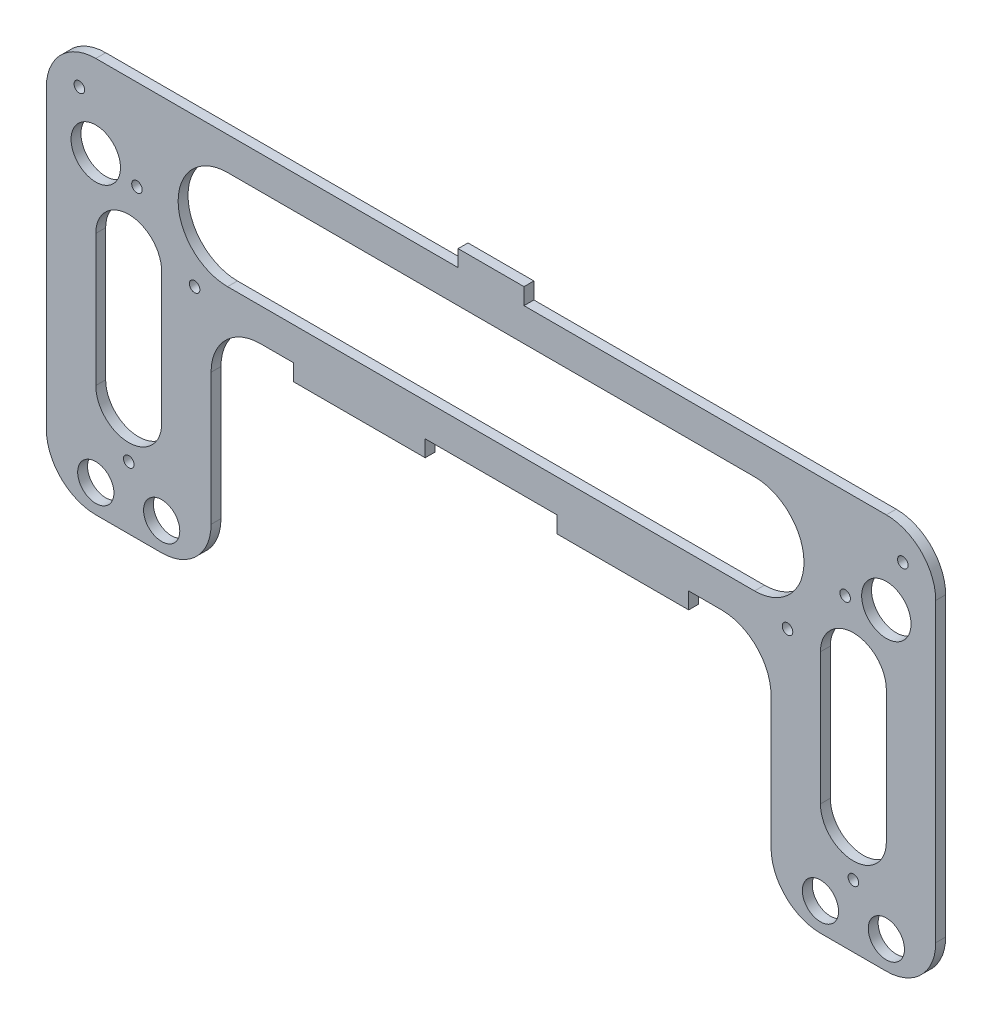
SolidWorks part; units mm, degrees
ref_plane "前视基准面" through (0, 0, 0) normal (0, 0, 1) x (1, 0, 0)
ref_plane "上视基准面" through (0, 0, 0) normal (0, 1, 0) x (1, 0, 0)
ref_plane "右视基准面" through (0, 0, 0) normal (1, 0, 0) x (0, 0, -1)
sketch "草图1" plane through (0, 0, 0) normal (0, 0, 1) x (1, 0, 0)
  line L0 (-120, 25) -> (-10, 25)
  line L4 (-125, 25) -> (0, 0) construction
  line L5 (125, 25) -> (0, 0) construction
  line L6 (0, 25) -> (0, 30) construction
  line L7 (-10, 25) -> (-10, 30)
  line L9 (-10, 30) -> (10, 30)
  line L10 (10, 25) -> (10, 30)
  line L11 (0, 25) -> (10, 30) construction
  line L12 (-10, 30) -> (0, 25) construction
  line L13 (-135, -35) -> (-203.9949, -103.9949) construction
  line L19 (10, 25) -> (120, 25)
  line L20 (-169.4975, -69.4975) -> (-204.8528, -34.1421) construction
  line L22 (-204.8528, -34.1421) -> (-151.5685, 19.1421) construction
  line L23 (-137.4264, 25) -> (-125, 25) construction
  line L24 (-204.8528, -34.1421) -> (-256.066, -85.3553) construction
  line L25 (-261.9239, -99.4975) -> (-261.9239, -99.8528) construction
  line L26 (261.9239, -99.4975) -> (261.9239, -99.8528) construction
  line L27 (204.8528, -34.1421) -> (256.066, -85.3553) construction
  line L28 (137.4264, 25) -> (125, 25) construction
  line L29 (204.8528, -34.1421) -> (151.5685, 19.1421) construction
  line L30 (169.4975, -69.4975) -> (204.8528, -34.1421) construction
  line L31 (218.1371, -109.8528) -> (251.9239, -109.8528) construction
  line L32 (135, -35) -> (203.9949, -103.9949) construction
  line L33 (-251.9239, -109.8528) -> (-218.1371, -109.8528) construction
  line L34 (-236.066, -111.9239) -> (-236.066, -65.3553) construction
  line L35 (-236.066, -111.9239) -> (-247.8859, -109.8528) construction
  line L36 (-247.8859, -109.8528) -> (-247.8859, -101.3528) construction
  line L37 (-247.8859, -101.3528) -> (-247.8859, -106.8528) construction
  line L38 (85, -40) -> (85, -80)
  line L39 (0, -25) -> (-20, -25)
  line L40 (-65, -25) -> (-65, -30) construction
  line L41 (-85, -30) -> (-45, -30) construction
  line L42 (-85, -30) -> (-85, -25) construction
  line L43 (-45, -30) -> (-45, -25) construction
  line L44 (45, -30) -> (45, -25) construction
  line L45 (85, -30) -> (85, -25) construction
  line L46 (85, -30) -> (45, -30) construction
  line L47 (65, -25) -> (65, -30) construction
  line L48 (-20, -25) -> (20, -25)
  line L49 (-20, -25) -> (20, -25) construction
  line L51 (-110, -95) -> (-110, -92)
  line L52 (-45, -30) -> (-20, -30)
  line L53 (-20, -30) -> (-20, -25)
  line L55 (-60, -25) -> (-60, -30)
  line L56 (-70, -25) -> (-60, -25)
  line L57 (-60, -30) -> (-45, -30)
  line L58 (20, -30) -> (20, -25)
  line L59 (45, -30) -> (20, -30)
  line L60 (60, -30) -> (45, -30)
  line L61 (60, -25) -> (60, -30)
  line L63 (70, -25) -> (60, -25)
  line L64 (-85, -40) -> (-85, -80)
  line L65 (-100, -95) -> (-120, -95)
  line L66 (-135, -80) -> (-135, 10)
  line L67 (-135, 25) -> (-125, 25)
  line L68 (100, -95) -> (120, -95)
  line L69 (135, -80) -> (135, 10)
  line L70 (135, 25) -> (125, 25)
  line L71 (-110, -92) -> (-110, -81)
  line L72 (-120, -86.5) -> (-100, -86.5)
  arc A0 (-251.9239, -109.8528) -> (-261.9239, -99.8528) centre (-251.9239, -99.8528) cw construction
  arc A2 (-137.4264, 25) -> (-151.5685, 19.1421) centre (-137.4264, 5) ccw construction
  arc A3 (-256.066, -85.3553) -> (-261.9239, -99.4975) centre (-241.9239, -99.4975) ccw construction
  arc A4 (-203.9949, -103.9949) -> (-218.1371, -109.8528) centre (-218.1371, -89.8528) cw construction
  arc A5 (203.9949, -103.9949) -> (218.1371, -109.8528) centre (218.1371, -89.8528) ccw construction
  arc A6 (256.066, -85.3553) -> (261.9239, -99.4975) centre (241.9239, -99.4975) cw construction
  arc A7 (137.4264, 25) -> (151.5685, 19.1421) centre (137.4264, 5) cw construction
  arc A9 (251.9239, -109.8528) -> (261.9239, -99.8528) centre (251.9239, -99.8528) ccw construction
  circle A12 centre (-247.8859, -101.3528) radius 5.5 construction
  circle A13 centre (-224.2461, -101.3528) radius 5.5 construction
  circle A14 centre (224.2461, -101.3528) radius 5.5 construction
  circle A15 centre (247.8859, -101.3528) radius 5.5 construction
  arc A16 (135, 10) -> (120, 25) centre (120, 10) ccw
  arc A17 (-120, 25) -> (-135, 10) centre (-120, 10) ccw
  arc A18 (85, -40) -> (70, -25) centre (70, -40) ccw
  arc A19 (-85, -40) -> (-70, -25) centre (-70, -40) cw
  arc A20 (120, -95) -> (135, -80) centre (120, -80) ccw
  arc A21 (100, -95) -> (85, -80) centre (100, -80) cw
  arc A22 (-100, -95) -> (-85, -80) centre (-100, -80) ccw
  arc A23 (-120, -95) -> (-135, -80) centre (-120, -80) cw
  circle A24 centre (-100, -86.5) radius 5.5
  circle A25 centre (-120, -86.5) radius 5.5
  circle A26 centre (120, -86.5) radius 5.5
  circle A27 centre (100, -86.5) radius 5.5
  point P1 (0, 0)
  point P20 (-259.8528, -109.8528)
  point P30 (-209.8528, -109.8528)
  point P48 (209.8528, -109.8528)
  point P49 (259.8528, -109.8528)
  point P68 (-65, -30)
  point P76 (65, -30)
  point P101 (135, -95)
  point P104 (85, -95)
  point P107 (-85, -95)
  point P110 (-135, -95)
  point P117 (-110, -86.5)
  dimension "D7" = 10
  dimension "D8" = 3
  dimension "D11" = 5.5
  dimension "D12" = 65
  dimension "D16" = 40
  dimension "D19" = 11
  dimension "D2" = 15
  dimension "D5" = 15
  dimension "D20" = 11
  dimension "D21" = 11
  dimension "D3" = 5
  dimension "D4" = 50
  dimension "D6" = 50
  dimension "D9" = 12
  dimension "D10" = 8.5
  dimension "D13" = 5
  dimension "D14" = 20
  dimension "D15" = 25
  dimension "D17" = 70
  dimension "D18" = 50
extrude "凸台-拉伸1" add sketch "草图1" along normal mid plane 3
sketch "草图2" plane through (0, 0, 1.5) normal (0, 0, 1) x (1, 0, 0)
  line L0 (-80, 0) -> (80, 0) construction
  line L1 (-110, -21) -> (-110, -61) construction
  line L2 (-80, 15) -> (80, 15)
  line L3 (-80, -15) -> (80, -15)
  line L4 (-110, -81) -> (-110, -41)
  line L7 (0, -15) -> (0, 15) construction
  line L8 (-100, -21) -> (-100, -61)
  line L11 (-120, 10) -> (-70, -40) construction
  line L12 (-95, -15) -> (-120, 10) construction
  line L13 (-95, -15) -> (-85, -25)
  line L16 (-120, 10) -> (-125, 15)
  line L17 (-80, 0) -> (-120, 0) construction
  line L20 (-120, -21) -> (-120, -61)
  line L21 (110, -21) -> (110, -61) construction
  line L22 (100, -21) -> (100, -61)
  line L23 (120, -21) -> (120, -61)
  line L24 (-110, -81) -> (-110, -71)
  arc A0 (-80, 15) -> (-80, -15) centre (-80, 0) ccw
  arc A1 (80, -15) -> (80, 15) centre (80, 0) ccw
  circle A26 centre (-107.5, -2.5) radius 1.6
  circle A27 centre (-90, -20) radius 1.6
  circle A28 centre (90, -20) radius 1.6
  circle A29 centre (107.5, -2.5) radius 1.6
  circle A31 centre (-125, 15) radius 1.6
  circle A32 centre (-120, 0) radius 7.5
  circle A33 centre (125, 15) radius 1.6
  circle A34 centre (120, 0) radius 7.5
  arc A37 (-100, -21) -> (-120, -21) centre (-110, -21) ccw
  arc A38 (-120, -61) -> (-100, -61) centre (-110, -61) ccw
  arc A39 (100, -21) -> (120, -21) centre (110, -21) cw
  arc A40 (120, -61) -> (100, -61) centre (110, -61) cw
  circle A41 centre (-110, -76) radius 1.6
  circle A42 centre (110, -76) radius 1.6
  point P5 (0, 0)
  point P12 (-110, -41)
  point P17 (-137.4264, 5)
  point P20 (110, -41)
  dimension "D1" = 40
  dimension "D2" = 3.2
  dimension "D3" = 3.2
  dimension "D4" = 3.2
  dimension "D5" = 3.2
  dimension "D6" = 15
extrude "切除-拉伸1" cut sketch "草图2" against normal blind 10 and the other way through all
